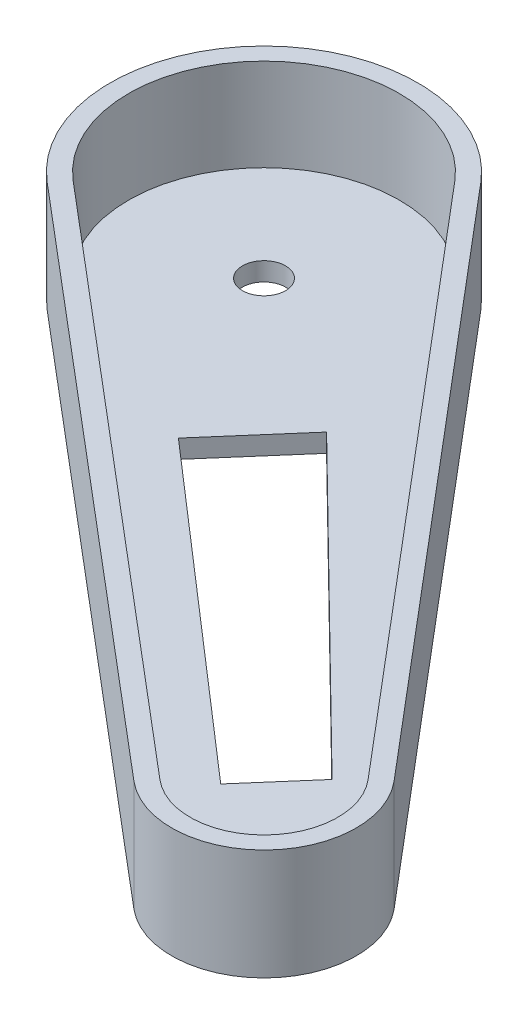
SolidWorks part; units mm, degrees
ref_plane "前视基准面" through (0, 0, 0) normal (0, 0, 1) x (1, 0, 0)
ref_plane "上视基准面" through (0, 0, 0) normal (0, 1, 0) x (1, 0, 0)
ref_plane "右视基准面" through (0, 0, 0) normal (1, 0, 0) x (0, 0, -1)
other "Configuration Table"
sketch "草图2" plane through (0, 0, 0) normal (0, 1, 0) x (1, 0, 0)
  line L0 (-140.5033, 0) -> (6884.6605, 0) construction
  line L1 (0, -140.5033) -> (0, 6884.6605) construction
  line L2 (0, 0) -> (42.4264, -42.4264)
  line L3 (42.4264, -42.4264) -> (-42.4264, 42.4264)
  line L4 (-58.5694, 23.3371) -> (32.7406, -53.88)
  line L5 (-23.3371, 58.5694) -> (53.88, -32.7406)
  circle A0 centre (-42.4264, 42.4264) radius 25
  circle A1 centre (42.4264, -42.4264) radius 15
  dimension "D3" = 50
  dimension "D4" = 30
  dimension "D1" = 60
  dimension "D2" = 120
extrude "凸台-拉伸2" add sketch "草图2" along normal blind 3
sketch "草图4" plane through (0, 3, 0) normal (0, 1, 0) x (1, 0, 0)
  line L0 (-58.5694, 23.3371) -> (32.7406, -53.88)
  line L1 (-58.5694, 23.3371) -> (32.7406, -53.88) construction
  line L2 (-23.3371, 58.5694) -> (53.88, -32.7406)
  line L3 (-23.3371, 58.5694) -> (53.88, -32.7406) construction
  line L4 (-56.6323, 25.6278) -> (34.6777, -51.5893)
  line L5 (-25.6278, 56.6323) -> (51.5893, -34.6777)
  circle A0 centre (-42.4264, 42.4264) radius 25
  circle A1 centre (42.4264, -42.4264) radius 15
  circle A2 centre (-42.4264, 42.4264) radius 22
  circle A3 centre (42.4264, -42.4264) radius 12
  circle A4 centre (-42.4264, 42.4264) radius 2.25
  circle A5 centre (42.4264, -42.4264) radius 2.5
  point P26 (0, 0)
  dimension "D3" = 4.5
  dimension "D4" = 5
  dimension "D1" = 3
  dimension "D2" = 3
extrude "切除-拉伸2" cut sketch "草图4" against normal through all contours A4 | A5
sketch "草图6" plane through (0, 3, 0) normal (0, 1, 0) x (1, 0, 0)
  circle A0 centre (-42.4264, 42.4264) radius 3.5
  dimension "D1" = 7
extrude "切除-拉伸3" cut sketch "草图6" against normal through all
sketch "草图7" plane through (0, 3, 0) normal (0, 1, 0) x (1, 0, 0)
  circle A0 centre (42.4264, -42.4264) radius 3.5
  dimension "D1" = 7
extrude "切除-拉伸4" cut sketch "草图7" against normal through all
sketch "草图8" plane through (0, 3, 0) normal (0, 1, 0) x (1, 0, 0)
  line L0 (-11.8521, 30.3069) -> (-26.8914, 12.9805)
  line L1 (-26.8914, 12.9805) -> (25.2188, -32.2512)
  line L2 (25.2188, -32.2512) -> (33.6267, -22.5647)
  line L3 (33.6267, -22.5647) -> (-15.703, 25.8704)
extrude "切除-拉伸5" cut sketch "草图8" against normal through all contours L2 L3 L0 L1
sketch "草图9" plane through (0, 3, 0) normal (0, 1, 0) x (1, 0, 0)
  line L0 (-23.3371, 58.5694) -> (53.88, -32.7406)
  line L1 (-58.5694, 23.3371) -> (32.7406, -53.88)
  line L2 (-56.6323, 25.6278) -> (34.6777, -51.5893)
  line L3 (-25.6278, 56.6323) -> (51.5893, -34.6777)
  circle A0 centre (-42.4264, 42.4264) radius 25
  circle A1 centre (42.4264, -42.4264) radius 15
  circle A2 centre (-42.4264, 42.4264) radius 22
  circle A3 centre (42.4264, -42.4264) radius 12
  line M8 (-58.5694, 23.3371) -> (32.7406, -53.88)
  arc M9 (32.7406, -53.88) -> (53.88, -32.7406) centre (42.4264, -42.4264) ccw
  line M10 (53.88, -32.7406) -> (-23.3371, 58.5694)
  arc M11 (-23.3371, 58.5694) -> (-58.5694, 23.3371) centre (-42.4264, 42.4264) ccw
  dimension "D1" = 3
  dimension "D2" = 3
extrude "凸台-拉伸4" add sketch "草图9" along normal blind 15 contours A2 L3 A0 L2 M11 | A1 A0 L3 M10 | A1 L2 A0 M8 | A3 L2 A1 L3 M9
